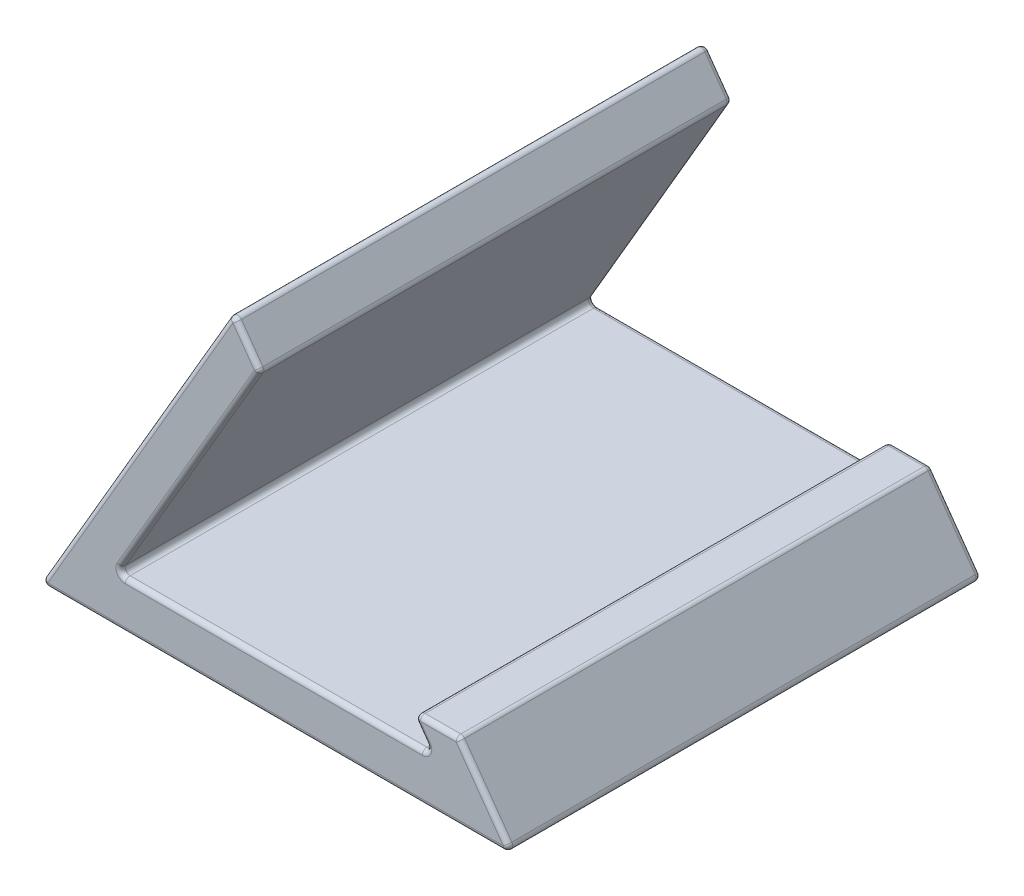
SolidWorks part; units mm, degrees
ref_plane "Front Plane" through (0, 0, 0) normal (0, 0, 1) x (1, 0, 0)
ref_plane "Top Plane" through (0, 0, 0) normal (0, 1, 0) x (1, 0, 0)
ref_plane "Right Plane" through (0, 0, 0) normal (1, 0, 0) x (0, 0, -1)
sketch "Sketch1" plane through (0, 0, 0) normal (0, 0, 1) x (1, 0, 0)
  line L0 (-22.379, 0) -> (27.621, 0)
  line L1 (27.621, 0) -> (21.9192, 8)
  line L2 (21.9192, 8) -> (16.9192, 8)
  line L3 (16.9192, 8) -> (19.0573, 5)
  line L4 (19.0573, 5) -> (-14.1898, 5)
  line L5 (-14.1898, 5) -> (0.9166, 30.919)
  line L6 (0.9166, 30.919) -> (-1.9854, 34.9907)
  line L7 (-1.9854, 34.9907) -> (-22.379, 0)
  point P8 (0, 0)
  point P11 (0, 0)
  point P12 (0, 0)
  point P13 (-23.1172, 0)
  dimension "D1" = 50
  dimension "D2" = 8
  dimension "D3" = 3
  dimension "D4" = 5
  dimension "D5" = 40.5
  dimension "D6" = 5
  dimension "D7" = 30
extrude "Boss-Extrude1" add sketch "Sketch1" along normal blind 50
fillet "Fillet1" radius 0.5 24 edges at (-12.1822, 17.4954, 50) (-22.379, 0, 25) (27.621, 0, 25) (2.621, 0, 50) (24.7701, 4, 50) (2.621, 0, 0) (24.7701, 4, 0) (21.9192, 8, 25) (16.9192, 8, 25) (19.0573, 5, 25) (-14.1898, 5, 25) (-6.6366, 17.9595, 50) (2.4338, 5, 50) (17.9883, 6.5, 50) (19.4192, 8, 50) (-12.1822, 17.4954, 0) (-6.6366, 17.9595, 0) (2.4338, 5, 0) (17.9883, 6.5, 0) (19.4192, 8, 0) (-0.5344, 32.9549, 0) (-0.5344, 32.9549, 50) (0.9166, 30.919, 25) (-1.9854, 34.9907, 25)
sketch "Sketch2" plane through (-16.7046, 9.7359, 0) normal (-0.864, 0.5035, 0) x (0, 0, 1)
  line L0 (3.691, 9.0291) -> (46.5198, 9.0291) construction
  text T0 "InnoCAD" font "Century Gothic" height 5
extrude "Cut-Extrude1" cut sketch "Sketch2" against normal blind 0.1
